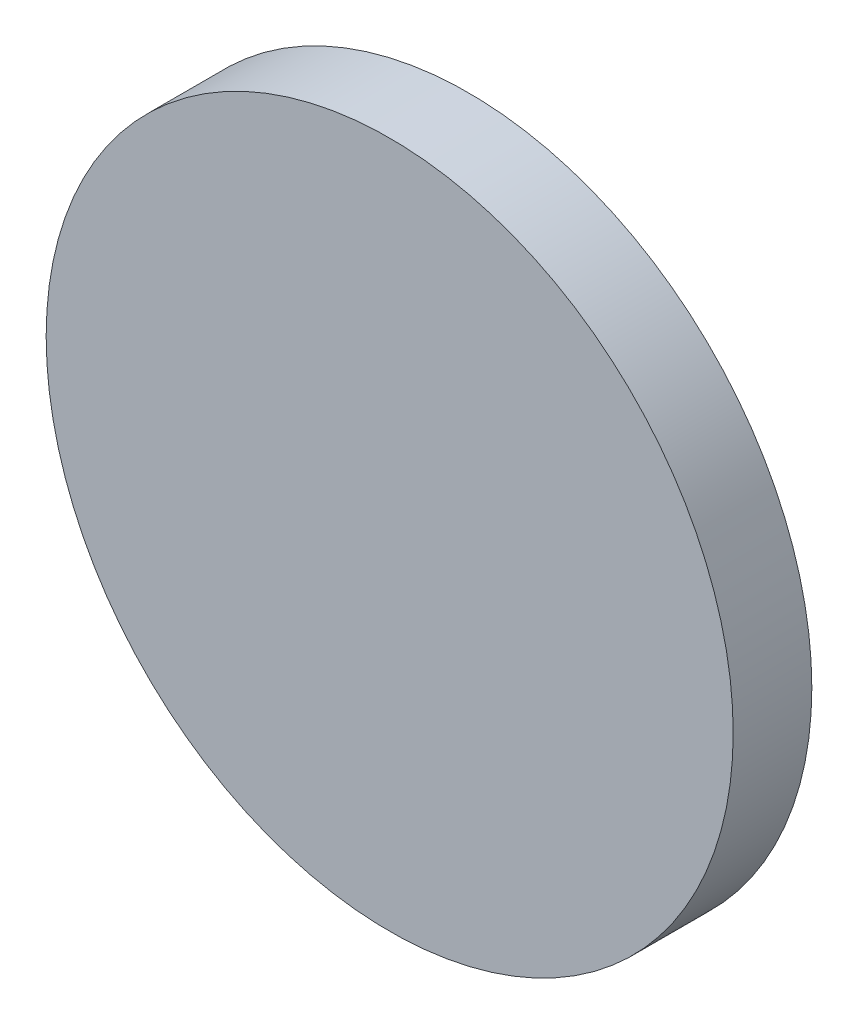
SolidWorks part; units mm, degrees
ref_plane "Front Plane" through (0, 0, 0) normal (0, 0, 1) x (1, 0, 0)
ref_plane "Top Plane" through (0, 0, 0) normal (0, 1, 0) x (1, 0, 0)
ref_plane "Right Plane" through (0, 0, 0) normal (1, 0, 0) x (0, 0, -1)
sketch "Sketch1" plane through (0, 0, 0) normal (0, 0, 1) x (1, 0, 0)
  circle A0 centre (0, 0) radius 0.0175
extrude "Boss-Extrude1" add sketch "Sketch1" against normal blind 0.004
